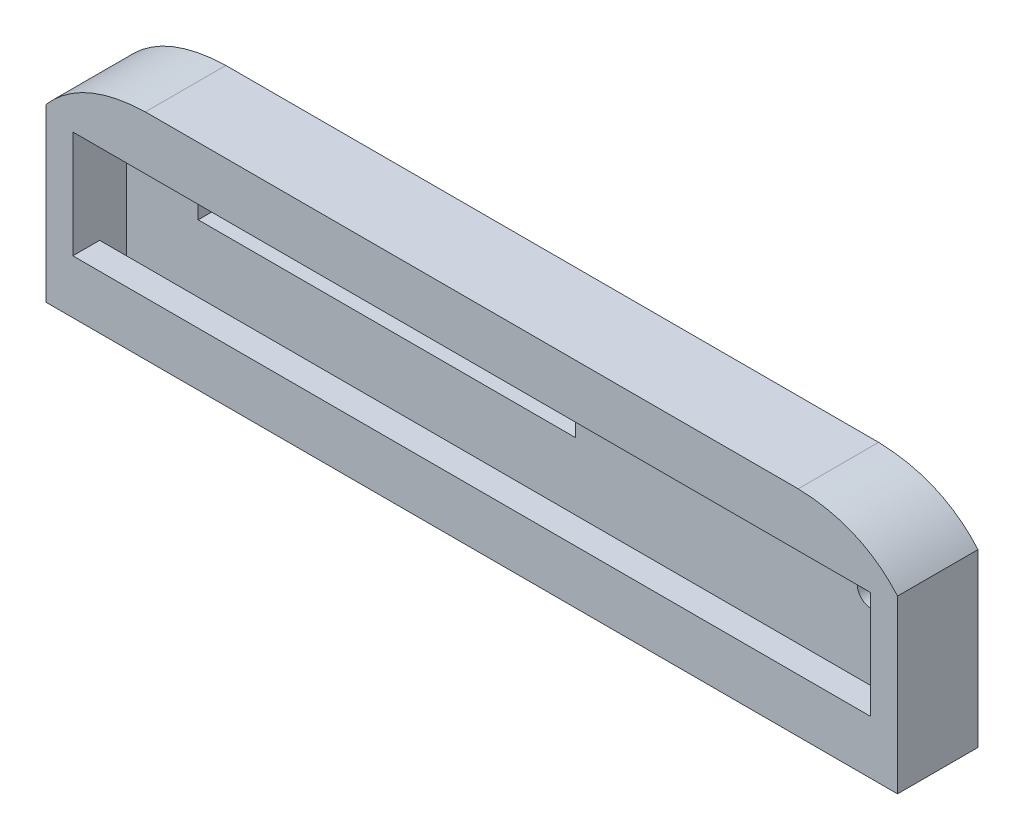
SolidWorks part; units mm, degrees
material "PE High Density"
ref_plane "Front Plane" through (0, 0, 0) normal (0, 0, 1) x (1, 0, 0)
ref_plane "Top Plane" through (0, 0, 0) normal (0, 1, 0) x (1, 0, 0)
ref_plane "Right Plane" through (0, 0, 0) normal (1, 0, 0) x (0, 0, -1)
sketch "Sketch1" plane through (0, 0, 0) normal (0, 0, 1) x (1, 0, 0)
  line L1 (-31.75, -8) -> (31.75, -8)
  line L2 (-31.75, -8) -> (-31.75, 8)
  line L3 (-31.75, 8) -> (31.75, 8)
  line L4 (31.75, -8) -> (31.75, 8)
  line L5 (-31.75, -8) -> (31.75, 8) construction
  line L6 (-31.75, 8) -> (31.75, -8) construction
  point P0 (0, 0)
  dimension "D1" = 63.5
  dimension "D2" = 16
extrude "Boss-Extrude1" add sketch "Sketch1" along normal blind 2
sketch "Sketch2" plane through (0, 0, 2) normal (0, 0, 1) x (1, 0, 0)
  line L1 (-31.75, 8) -> (31.75, 8)
  line L2 (-31.75, 8) -> (-31.75, -8)
  line L3 (-31.75, -8) -> (31.75, -8)
  line L4 (31.75, 8) -> (31.75, -8)
  line L5 (-31.75, 8) -> (31.75, -8) construction
  line L6 (-31.75, -8) -> (31.75, 8) construction
  line L7 (-29.75, 6) -> (29.75, 6)
  line L8 (-29.75, 6) -> (-29.75, -6)
  line L9 (-29.75, -6) -> (29.75, -6)
  line L10 (29.75, 6) -> (29.75, -6)
  line L11 (-29.75, 6) -> (29.75, -6) construction
  line L12 (-29.75, -6) -> (29.75, 6) construction
  point P0 (0, 0)
  point P7 (0, 0)
  dimension "D1" = 2
  dimension "D2" = 2
extrude "Boss-Extrude2" add sketch "Sketch2" along normal blind 2
sketch "Sketch4" plane through (0, 0, 4) normal (0, 0, 1) x (1, 0, 0)
  line L0 (29.75, -6) -> (29.75, 6) construction
  line L1 (-31.75, 8) -> (31.75, 8)
  line L2 (-31.75, 8) -> (-31.75, -8)
  line L3 (-31.75, -8) -> (31.75, -8)
  line L4 (31.75, 8) -> (31.75, -8)
  line L5 (-31.75, 8) -> (31.75, -8) construction
  line L6 (-31.75, -8) -> (31.75, 8) construction
  line L7 (-29.75, 4) -> (29.75, 4)
  line L8 (-29.75, 4) -> (-29.75, -4)
  line L9 (-29.75, -4) -> (29.75, -4)
  line L10 (29.75, 4) -> (29.75, -4)
  line L11 (-29.75, 4) -> (29.75, -4) construction
  line L12 (-29.75, -4) -> (29.75, 4) construction
  line L13 (29.75, 6) -> (-29.75, 6) construction
  point P0 (0, 0)
  point P7 (0, 0)
  dimension "D1" = 2
extrude "Boss-Extrude3" add sketch "Sketch4" along normal blind 2
sketch "Sketch6" plane through (0, 0, 2) normal (0, 0, 1) x (1, 0, 0)
  line L0 (31.75, -8) -> (31.75, 8) construction
  line L1 (-31.75, -8) -> (31.75, -8) construction
  circle A0 centre (25.75, 0) radius 1
  dimension "D1" = 2
  dimension "D3" = 8
  dimension "D2" = 6
extrude "Cut-Extrude2" cut sketch "Sketch6" against normal through all
sketch "Sketch7" plane through (0, 0, 0) normal (0, 0, -1) x (-1, 0, 0)
  line L0 (-31.75, -8) -> (-31.75, 8) construction
  line L1 (-3.75, -1) -> (24.4, -1)
  line L2 (-3.75, -1) -> (-3.75, 1)
  line L3 (-3.75, 1) -> (24.4, 1)
  line L4 (24.4, -1) -> (24.4, 1)
  line L5 (31.75, 8) -> (31.75, -8) construction
  point P4 (-3.75, 0)
  dimension "D1" = 2
  dimension "D2" = 28
  dimension "D3" = 7.35
extrude "Cut-Extrude3" cut sketch "Sketch7" against normal through all
sketch "Sketch8" plane through (0, 0, 0) normal (0, 0, -1) x (-1, 0, 0)
  line L6 (-31.75, 8) -> (31.75, 8) construction
  line L7 (23.4154, 8) -> (23.4154, 10) construction
  line L8 (31.75, 8) -> (31.75, -8) construction
  line L9 (31.75, 4.7772) -> (31.75, 8)
  line L10 (31.75, 8) -> (23.4154, 8)
  spline S1 degree 2 poles (23.4154, 8) (28.8242, 8.154) (31.75, 4.7772) knots 0 0 0 1 1 1
  line M8 (31.75, -8) -> (31.75, 8)
  line M9 (31.75, 8) -> (-31.75, 8)
extrude "Cut-Extrude4" cut sketch "Sketch8" against normal through all contours S1 M9 M8
mirror "Mirror1" about plane through (0, 0, 0) normal (1, 0, 0) of "Cut-Extrude4"
